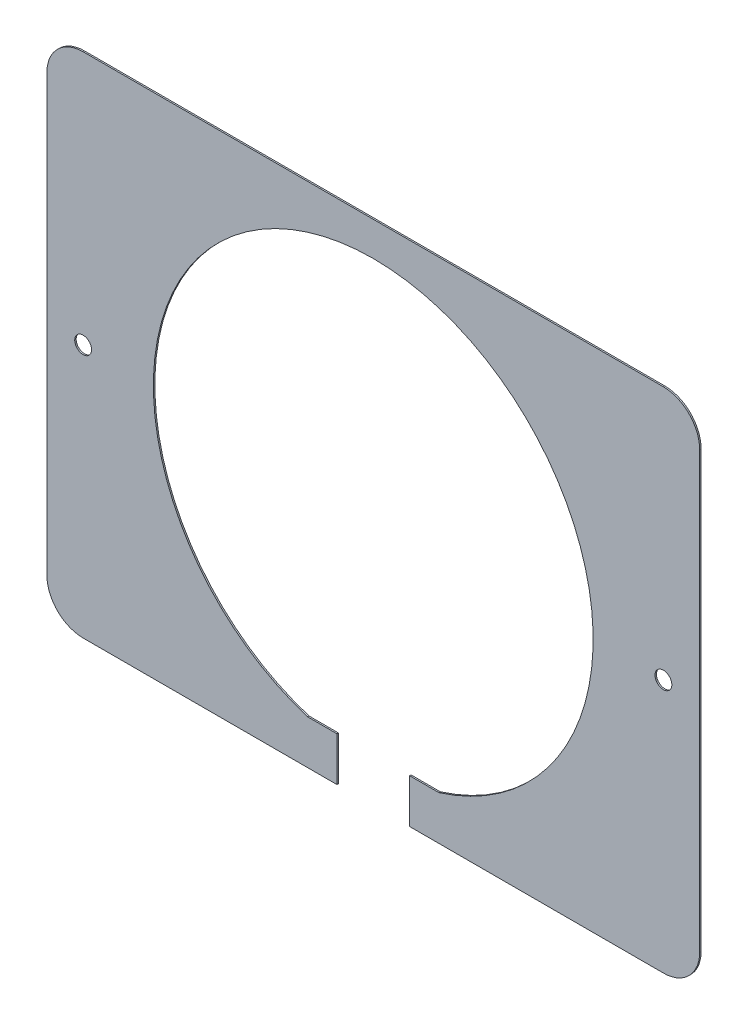
SolidWorks part; units mm, degrees
ref_plane "Front Plane" through (0, 0, 0) normal (0, 0, 1) x (1, 0, 0)
ref_plane "Top Plane" through (0, 0, 0) normal (0, 1, 0) x (1, 0, 0)
ref_plane "Right Plane" through (0, 0, 0) normal (1, 0, 0) x (0, 0, -1)
sketch "Sketch2" plane through (0, 0, 0) normal (0, 0, 1) x (1, 0, 0)
  line L0 (-11.5, -36.7423) -> (11.5, -36.7423)
  line L1 (0, 38.5) -> (0, -36.7423) construction
  line L2 (-50.8, 0) -> (0, 0) construction
  line L3 (-57.15, 44.45) -> (57.15, 44.45)
  line L4 (-57.15, 44.45) -> (-57.15, -44.45)
  line L5 (-57.15, -44.45) -> (57.15, -44.45)
  line L6 (57.15, 44.45) -> (57.15, -44.45)
  line L7 (-57.15, 44.45) -> (57.15, -44.45) construction
  line L8 (-57.15, -44.45) -> (57.15, 44.45) construction
  line L9 (0, 0) -> (50.8, 0) construction
  line L12 (-6.35, -36.7423) -> (-6.35, -44.45)
  line L13 (6.35, -36.7423) -> (6.35, -44.45)
  circle A0 centre (0, 0) radius 38.5
  circle A11 centre (-50.8, 0) radius 1.475
  circle A12 centre (50.8, 0) radius 1.475
  point P12 (100.1831, -73.028)
  dimension "D1" = 77
  dimension "D11" = 2.95
  dimension "D3" = 114.3
  dimension "D8" = 12.7
  dimension "D9" = 6.35
  dimension "D10" = 88.9
  dimension "D12" = 50.8
  dimension "D2" = 23
extrude "Boss-Extrude1" add sketch "Sketch2" along normal blind 0.254
fillet "Fillet1" radius 6.35 4 edges at (-57.15, -44.45, 0.127) (57.15, -44.45, 0.127) (57.15, 44.45, 0.127) (-57.15, 44.45, 0.127)
equation "\"D3@Sketch2\"=25.4*4.5"
equation "\"D9@Sketch2\"=\"D8@Sketch2\"/2"
